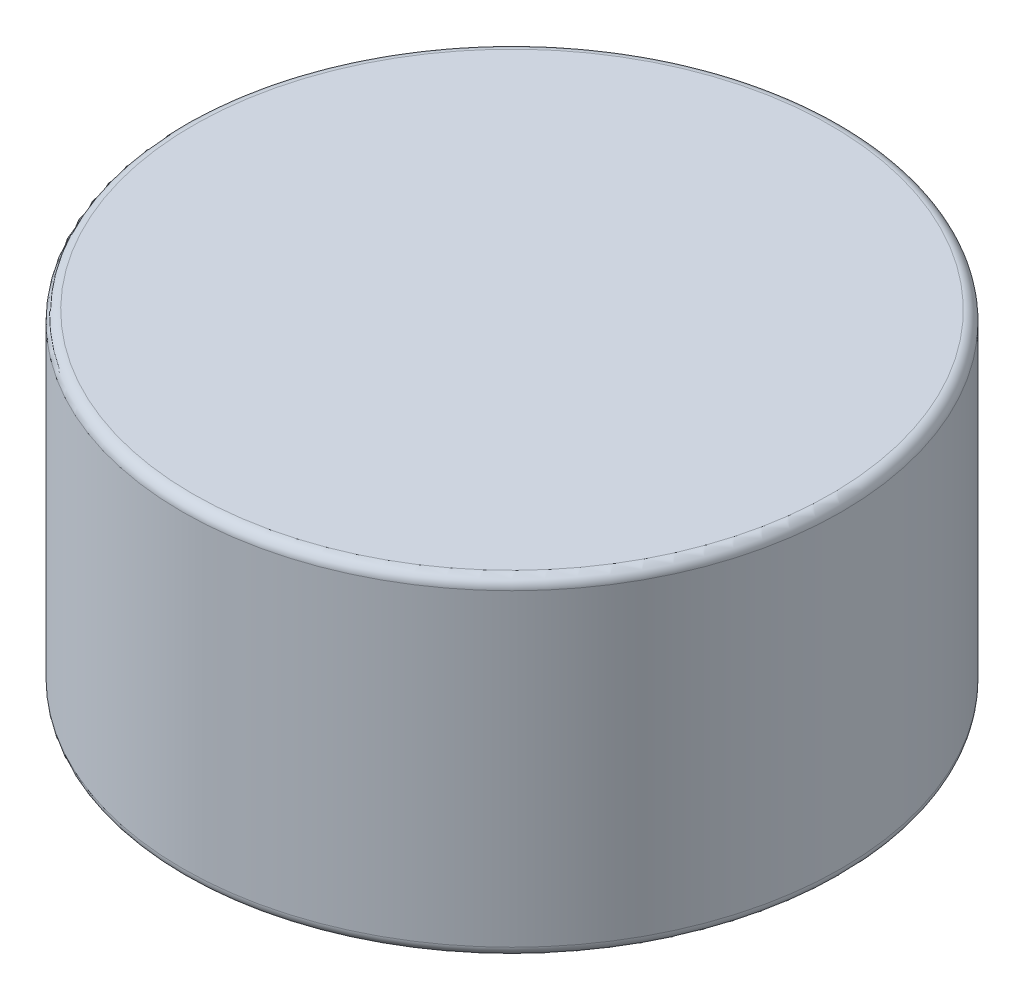
SolidWorks part; units mm, degrees
ref_plane "Front Plane" through (0, 0, 0) normal (0, 0, 1) x (1, 0, 0)
ref_plane "Top Plane" through (0, 0, 0) normal (0, 1, 0) x (1, 0, 0)
ref_plane "Right Plane" through (0, 0, 0) normal (1, 0, 0) x (0, 0, -1)
sketch "Sketch1" plane through (0, 0, 0) normal (0, 1, 0) x (1, 0, 0)
  circle A0 centre (0, 0) radius 3.175
  dimension "D1" = 6.35
extrude "Boss-Extrude1" add sketch "Sketch1" along normal blind 3.175
fillet "Fillet1" radius 0.1 2 edges at (0, 3.175, 3.175) (0, 0, 3.175)
